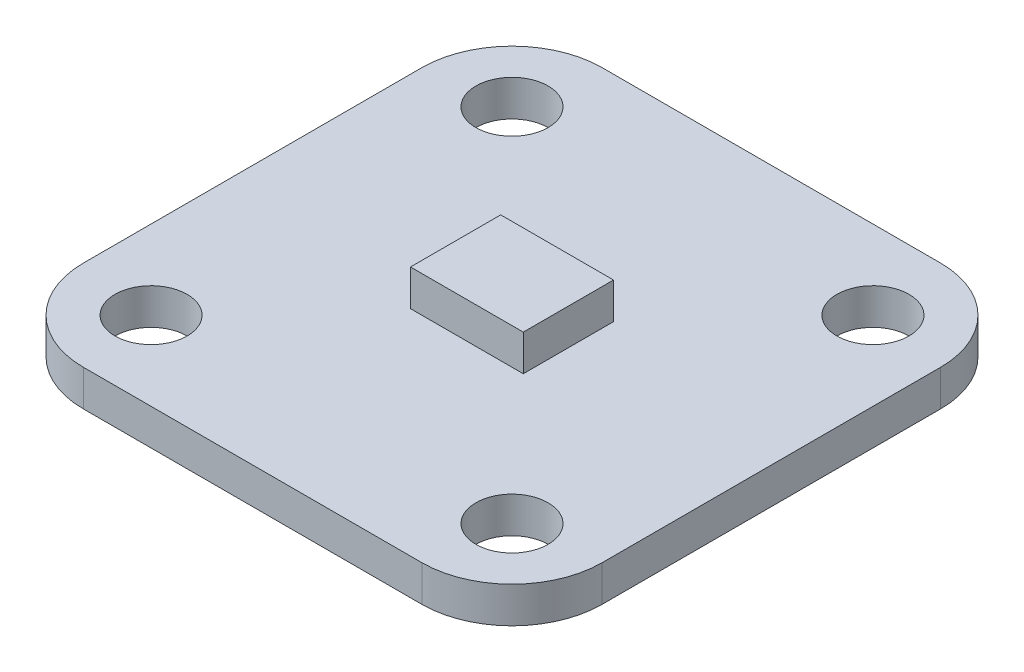
SolidWorks part; units mm, degrees
ref_plane "前视基准面" through (0, 0, 0) normal (0, 0, 1) x (1, 0, 0)
ref_plane "上视基准面" through (0, 0, 0) normal (0, 1, 0) x (1, 0, 0)
ref_plane "右视基准面" through (0, 0, 0) normal (1, 0, 0) x (0, 0, -1)
other "Configuration Table"
sketch "草图1" plane through (0, 0, 0) normal (0, 1, 0) x (1, 0, 0)
  line L1 (-11.5, -11.5) -> (11.5, -11.5)
  line L2 (-11.5, -11.5) -> (-11.5, 11.5)
  line L3 (-11.5, 11.5) -> (11.5, 11.5)
  line L4 (11.5, -11.5) -> (11.5, 11.5)
  line L5 (-11.5, -11.5) -> (11.5, 11.5) construction
  line L6 (-11.5, 11.5) -> (11.5, -11.5) construction
  point P0 (0, 0)
  dimension "D1" = 23
  dimension "D2" = 23
extrude "凸台-拉伸1" add sketch "草图1" along normal blind 1.6
sketch "草图2" plane through (0, 1.6, 0) normal (0, 1, 0) x (1, 0, 0)
  line L1 (-2.5, -2) -> (2.5, -2)
  line L2 (-2.5, -2) -> (-2.5, 2)
  line L3 (-2.5, 2) -> (2.5, 2)
  line L4 (2.5, -2) -> (2.5, 2)
  line L5 (-2.5, -2) -> (2.5, 2) construction
  line L6 (-2.5, 2) -> (2.5, -2) construction
  point P0 (0, 0)
  dimension "D1" = 5
  dimension "D2" = 4
extrude "凸台-拉伸2" add sketch "草图2" along normal blind 1.6
fillet "圆角1" radius 4 4 edges at (11.5, 0.8, -11.5) (-11.5, 0.8, -11.5) (11.5, 0.8, 11.5) (-11.5, 0.8, 11.5)
sketch "草图3" plane through (0, 0, 0) normal (0, -1, 0) x (1, 0, 0)
  line L1 (-8, -8) -> (8, -8) construction
  line L2 (-8, -8) -> (-8, 8) construction
  line L3 (-8, 8) -> (8, 8) construction
  line L4 (8, -8) -> (8, 8) construction
  line L5 (-8, -8) -> (8, 8) construction
  line L6 (-8, 8) -> (8, -8) construction
  circle A0 centre (-8, 8) radius 1.6
  circle A1 centre (8, 8) radius 1.6
  circle A2 centre (8, -8) radius 1.6
  circle A3 centre (-8, -8) radius 1.6
  point P0 (0, 0)
  point P7 (0, 0)
  point P16 (0, 0)
  dimension "D3" = 3.2
  dimension "D1" = 16
  dimension "D2" = 16
  dimension "D4" = 4
extrude "切除-拉伸1" cut sketch "草图3" against normal up to next
